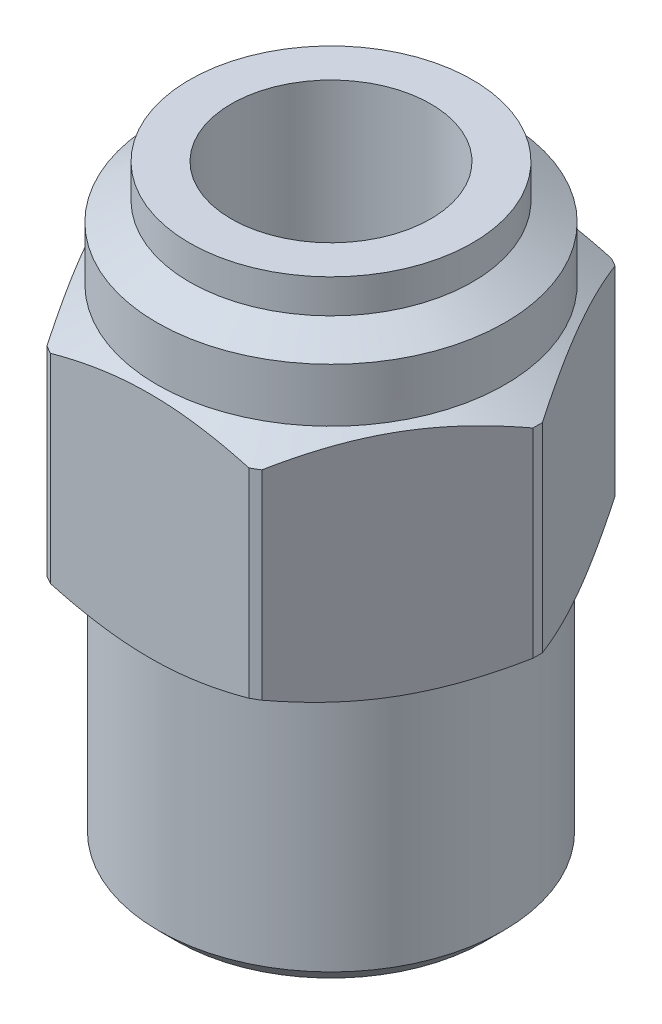
SolidWorks part; units mm, degrees
material "AISI 1010 Steel, hot rolled bar"
ref_plane "Front" through (0, 0, 0) normal (0, 0, 1) x (1, 0, 0)
ref_plane "Top" through (0, 0, 0) normal (0, 1, 0) x (1, 0, 0)
ref_plane "Right" through (0, 0, 0) normal (1, 0, 0) x (0, 0, -1)
sketch "Sketch1" plane through (0, 0, 0) normal (1, 0, 0) x (0, 0, -1)
  line L0 (0, 19.6306) -> (0, 0) construction
  line L1 (4.75, 0) -> (4.75, 7)
  line L2 (4.75, 7) -> (5.7, 7.5485)
  line L3 (5.7, 7.5485) -> (5.7, 13.0485)
  line L4 (5.7, 13.0485) -> (4.8, 13.5681)
  line L5 (4.8, 13.5681) -> (4.8, 15.0485)
  line L6 (4.8, 15.0485) -> (3.9, 15.5681)
  line L7 (3.9, 15.5681) -> (3.9, 16.5)
  line L8 (3.9, 16.5) -> (2.75, 16.5)
  line L9 (2.75, 16.5) -> (2.75, 10.2985)
  line L10 (4.75, 0) -> (3.3, 0)
  line L11 (3.3, 0) -> (3.3, 3.6)
  line L12 (3.3, 3.6) -> (2.2, 4.2351)
  line L13 (2.2, 4.2351) -> (2.2, 9.9809)
  line L14 (2.2, 9.9809) -> (2.75, 10.2985)
  point P5 (5.7, 10.2985)
  dimension "D1" = 9.5
  dimension "D2" = 7
  dimension "D3" = 60
  dimension "D4" = 11.4
  dimension "D5" = 9.6
  dimension "D6" = 60
  dimension "D7" = 5.5
  dimension "D8" = 2
  dimension "D9" = 16.5
  dimension "D10" = 7.8
  dimension "D11" = 5.5
  dimension "D12" = 6.6
  dimension "D13" = 3.6
  dimension "D14" = 60
  dimension "D15" = 4.4
  dimension "D16" = 60
revolve "Revolve1" add sketch "Sketch1" angle 360 about L0
sketch "Sketch2" plane through (0, 16.5, 0) normal (0, 1, 0) x (1, 0, 0)
  line L1 (2.8868, 5) -> (-2.8868, 5)
  line L2 (-2.8868, 5) -> (-5.7735, 0)
  line L3 (-5.7735, 0) -> (-2.8868, -5)
  line L4 (-2.8868, -5) -> (2.8868, -5)
  line L5 (2.8868, -5) -> (5.7735, 0)
  line L6 (5.7735, 0) -> (2.8868, 5)
  circle A0 centre (0, 0) radius 5 construction
  circle A1 centre (0, 0) radius 5.7735
  dimension "D1" = 10
extrude "Cut-Extrude1" cut sketch "Sketch2" against normal through all contours L1 A1 | L2 A1 | L3 A1 | L4 A1 | L5 A1 | L6 A1
chamfer "Chamfer1" distance 0.5 angle 45 1 edges at (0, 0, 4.75)
